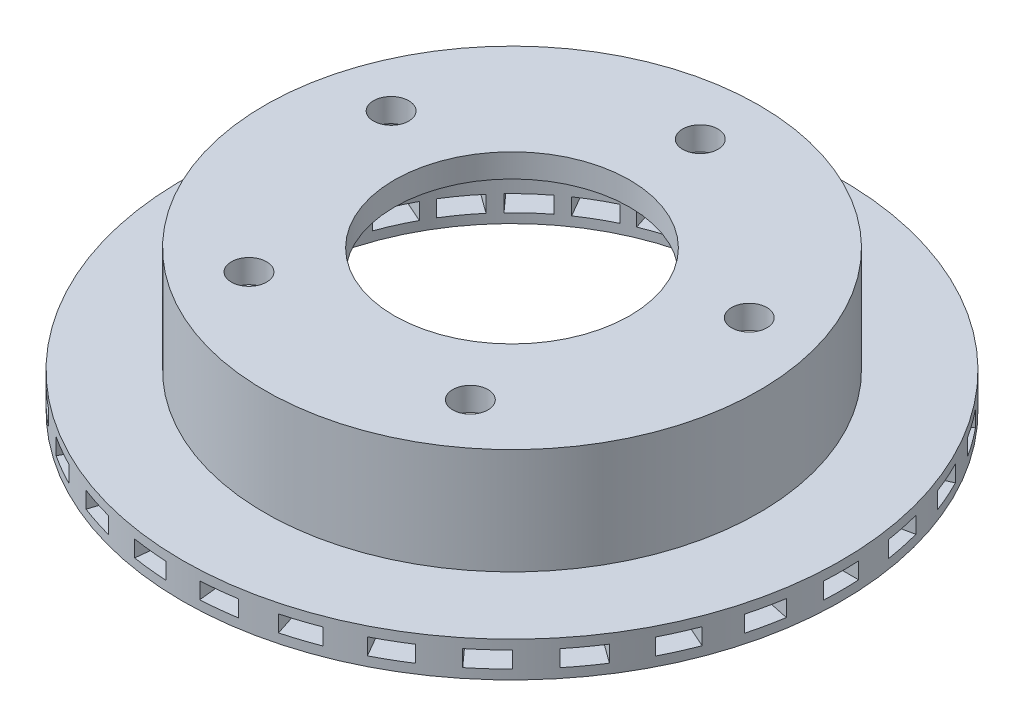
SolidWorks part; units mm, degrees
ref_plane "Front Plane" through (0, 0, 0) normal (0, 0, 1) x (1, 0, 0)
ref_plane "Top Plane" through (0, 0, 0) normal (0, 1, 0) x (1, 0, 0)
ref_plane "Right Plane" through (0, 0, 0) normal (1, 0, 0) x (0, 0, -1)
sketch "Sketch1" plane through (0, 0, 0) normal (0, 1, 0) x (1, 0, 0)
  circle A0 centre (0, 0) radius 140
  dimension "D1" = 280
extrude "Boss-Extrude1" add sketch "Sketch1" along normal mid plane 15
sketch "Sketch2" plane through (0, 7.5, 0) normal (0, 1, 0) x (1, 0, 0)
  circle A0 centre (0, 0) radius 97.5
  dimension "D1" = 195
extrude "Cut-Extrude1" cut sketch "Sketch2" against normal through all both and the other way through all
sketch "Sketch3" plane through (0, 7.5, 0) normal (0, 1, 0) x (1, 0, 0)
  circle A0 centre (0, 0) radius 105
  dimension "D1" = 210
extrude "Boss-Extrude2" add sketch "Sketch3" along normal blind 45
sketch "Sketch5" plane through (0, 52.5, 0) normal (0, 1, 0) x (1, 0, 0)
  circle A0 centre (0, 0) radius 50
  dimension "D1" = 100
extrude "Cut-Extrude2" cut sketch "Sketch5" against normal through all
sketch "Sketch6" plane through (0, 52.5, 0) normal (0, 1, 0) x (1, 0, 0)
  line L0 (-105, 0) -> (105, 0) construction
  circle A0 centre (0, 0) radius 105 construction
  circle A1 centre (0, 0) radius 105 construction
sketch "Sketch7" plane through (0, 52.5, 0) normal (0, 1, 0) x (1, 0, 0)
  circle A0 centre (0, 0) radius 80 construction
  circle A1 centre (0, 80) radius 7.5
  dimension "D1" = 160
  dimension "D2" = 15
extrude "Cut-Extrude3" cut sketch "Sketch7" against normal through all both and the other way through all
pattern_circular "CirPattern1" count 5 over 360 about axis through (0, 0, 0) along (0, 1, 0) of "Cut-Extrude3"
ref_plane "Plane1" through (140, 0, 0) normal (1, 0, 0) x (0, 0, -1)
sketch "Sketch9" plane through (140, 0, 0) normal (1, 0, 0) x (0, 0, -1)
  line L1 (7.5, 3.5) -> (-7.5, 3.5)
  line L2 (7.5, 3.5) -> (7.5, -3.5)
  line L3 (7.5, -3.5) -> (-7.5, -3.5)
  line L4 (-7.5, 3.5) -> (-7.5, -3.5)
  line L5 (7.5, 3.5) -> (-7.5, -3.5) construction
  line L6 (7.5, -3.5) -> (-7.5, 3.5) construction
  point P0 (0, 0)
  dimension "D1" = 15
  dimension "D2" = 7
extrude "Cut-Extrude4" cut sketch "Sketch9" against normal through all both and the other way through all
pattern_circular "CirPattern2" count 30 over 360 about axis through (0, 0, 0) along (0, 1, 0) of "Cut-Extrude4"
sketch "Sketch11" plane through (0, 7.5, 0) normal (0, -1, 0) x (1, 0, 0)
  circle A0 centre (0, 0) radius 96.8738
extrude "Cut-Extrude5" cut sketch "Sketch11" against normal blind 35
sketch "Sketch12" plane through (0, 7.5, 0) normal (0, -1, 0) x (1, 0, 0)
  circle A0 centre (0, 0) radius 97.5
extrude "Cut-Extrude6" cut sketch "Sketch12" against normal blind 35
